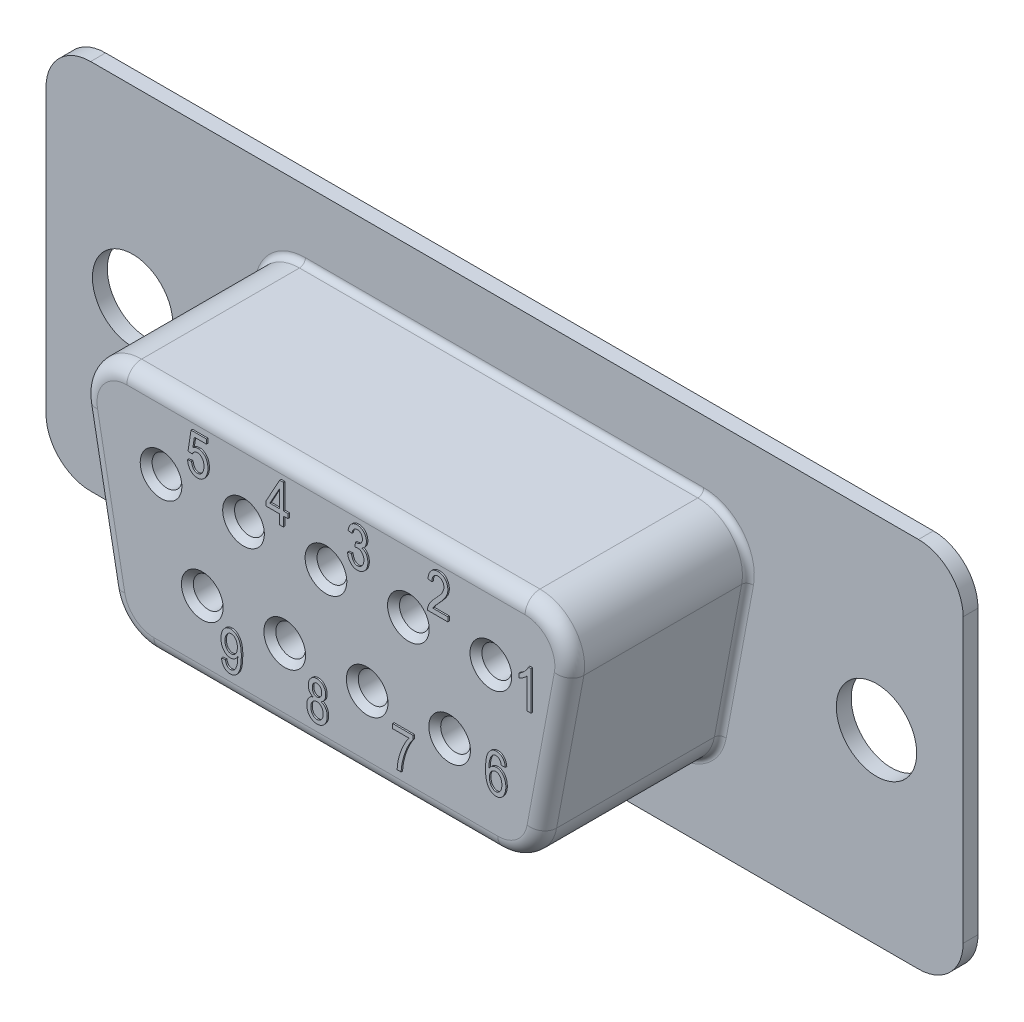
SolidWorks part; units mm, degrees
material "1023 Chapa de aço carbono (SS)"
ref_plane "Plano frontal" through (0, 0, 0) normal (0, 0, 1) x (1, 0, 0)
ref_plane "Plano superior" through (0, 0, 0) normal (0, 1, 0) x (1, 0, 0)
ref_plane "Plano direito" through (0, 0, 0) normal (1, 0, 0) x (0, 0, -1)
sketch "Esboço2" plane through (0, 0, 0) normal (0, 0, 1) x (1, 0, 0)
  line L0 (-13.905, 6.25) -> (13.905, 6.25)
  line L1 (15.405, 4.75) -> (15.405, -4.75)
  line L2 (13.905, -6.25) -> (-13.905, -6.25)
  line L3 (-15.405, -4.75) -> (-15.405, 4.75)
  line L4 (0, 6.25) -> (0, 0) construction
  line L5 (0, 0) -> (15.405, 0) construction
  arc A0 (13.905, 6.25) -> (15.405, 4.75) centre (13.905, 4.75) cw
  arc A1 (15.405, -4.75) -> (13.905, -6.25) centre (13.905, -4.75) cw
  arc A2 (-13.905, -6.25) -> (-15.405, -4.75) centre (-13.905, -4.75) cw
  arc A3 (-15.405, 4.75) -> (-13.905, 6.25) centre (-13.905, 4.75) cw
  dimension "D3" = 1.5
  dimension "D4" = 1.5
  dimension "D5" = 1.5
  dimension "D6" = 1.5
  dimension "D1" = 30.81
  dimension "D2" = 12.5
extrude "Ressalto-extrusão1" add sketch "Esboço2" along normal blind 0.5
sketch "Esboço3" plane through (0, 0, 0.5) normal (0, 0, 1) x (1, 0, 0)
  line L0 (0, 0) -> (12.495, 0) construction
  circle A0 centre (12.495, 0) radius 1.35
  dimension "D2" = 2.7
  dimension "D1" = 12.495
extrude "Corte-extrusão1" cut sketch "Esboço3" against normal through all
mirror "Espelhar1" about plane through (0, 0, 0) normal (1, 0, 0) of "Corte-extrusão1"
sketch "Esboço4" plane through (0, 0, 0.5) normal (0, 0, 1) x (1, 0, 0)
  line L0 (-6.6905, 3.95) -> (6.6905, 3.95)
  line L1 (8.165, 2.1747) -> (7.25, -2.7253)
  line L2 (5.7755, -3.95) -> (-5.7755, -3.95)
  line L3 (-7.25, -2.7253) -> (-8.165, 2.1747)
  line L4 (0, 3.95) -> (0, 0) construction
  line L5 (0, -3.95) -> (0, 3.95) construction
  arc A0 (6.6905, 3.95) -> (8.165, 2.1747) centre (6.6905, 2.45) cw
  arc A1 (7.25, -2.7253) -> (5.7755, -3.95) centre (5.7755, -2.45) cw
  arc A2 (-5.7755, -3.95) -> (-7.25, -2.7253) centre (-5.7755, -2.45) cw
  arc A3 (-8.165, 2.1747) -> (-6.6905, 3.95) centre (-6.6905, 2.45) cw
  dimension "D1" = 1.5
  dimension "D2" = 1.5
  dimension "D3" = 1.5
  dimension "D4" = 1.5
  dimension "D5" = 7.9
  dimension "D6" = 16.33
  dimension "D7" = 14.5
  dimension "D8" = 3.95
extrude "Ressalto-extrusão2" add sketch "Esboço4" along normal blind 6
sketch "Esboço5" plane through (0, 0, 6.5) normal (0, 0, 1) x (1, 0, 0)
  line L0 (0, 1.42) -> (0, 0) construction
  circle A0 centre (0, 1.42) radius 0.5
  dimension "D1" = 1
  dimension "D2" = 1.42
extrude "Corte-extrusão2" cut sketch "Esboço5" against normal through all
chamfer "Chanfro1" distance 0.2 angle 45 1 edges at (0.5, 1.42, 6.5)
pattern_linear "Padrão linear1" count 3 spacing 2.77 along (1, 0, 0) count 3 spacing 2.77 along (-1, 0, 0) of "Corte-extrusão2", "Chanfro1"
sketch "Esboço6" plane through (0, 0, 6.5) normal (0, 0, 1) x (1, 0, 0)
  circle A0 centre (-1.385, -1.42) radius 0.5
  dimension "D1" = 1
  dimension "D2" = 1.385
  dimension "D3" = 1.42
extrude "Corte-extrusão3" cut sketch "Esboço6" against normal through all
chamfer "Chanfro2" distance 0.2 angle 45 1 edges at (-0.885, -1.42, 6.5)
pattern_linear "Padrão linear2" count 3 spacing 2.77 along (1, 0, 0) count 2 spacing 2.77 along (-1, 0, 0) of "Corte-extrusão3", "Chanfro2"
fillet "Filete1" radius 0.5 8 edges at (-6.7339, -3.6039, 6.5) (-7.7075, -0.2753, 6.5) (-7.8444, 3.4084, 6.5) (0, 3.95, 6.5) (7.8444, 3.4084, 6.5) (7.7075, -0.2753, 6.5) (6.7339, -3.6039, 6.5) (0, -3.95, 6.5)
fillet "Filete2" radius 0.2 8 edges at (7.8444, 3.4084, 0.5) (7.7075, -0.2753, 0.5) (6.7339, -3.6039, 0.5) (0, -3.95, 0.5) (-6.7339, -3.6039, 0.5) (-7.7075, -0.2753, 0.5) (-7.8444, 3.4084, 0.5) (0, 3.95, 0.5)
sketch "Esboço7" plane through (0, 0, 6.5) normal (0, 0, 1) x (1, 0, 0)
  text T0 "1" font "Arial Narrow" height in points 5
  text T1 "5432" font "Arial Narrow" height in points 5
  text T2 "987" font "Arial Narrow" height in points 5
  text T3 "6" font "Arial Narrow" height in points 5
extrude "Ressalto-extrusão3" add sketch "Esboço7" along normal blind 0.05
sketch "Esboço8" plane through (0, 0, 0) normal (0, 0, -1) x (-1, 0, 0)
  circle A0 centre (-5.54, 1.42) radius 0.5
  circle A1 centre (-5.54, 1.42) radius 0.45
  dimension "D1" = 1
  dimension "D2" = 0.9
extrude "Ressalto-extrusão4" add sketch "Esboço8" against normal blind 5
pattern_linear "Padrão linear3" count 5 spacing 2.77 along (-1, 0, 0) of "Ressalto-extrusão4"
sketch "Esboço9" plane through (0, 0, 0) normal (0, 0, -1) x (-1, 0, 0)
  circle A0 centre (-4.155, -1.42) radius 0.5
  circle A1 centre (-4.155, -1.42) radius 0.45
  dimension "D1" = 1
  dimension "D2" = 0.9
extrude "Ressalto-extrusão5" add sketch "Esboço9" against normal blind 5
pattern_linear "Padrão linear4" count 4 spacing 2.77 along (-1, 0, 0) of "Ressalto-extrusão5"
